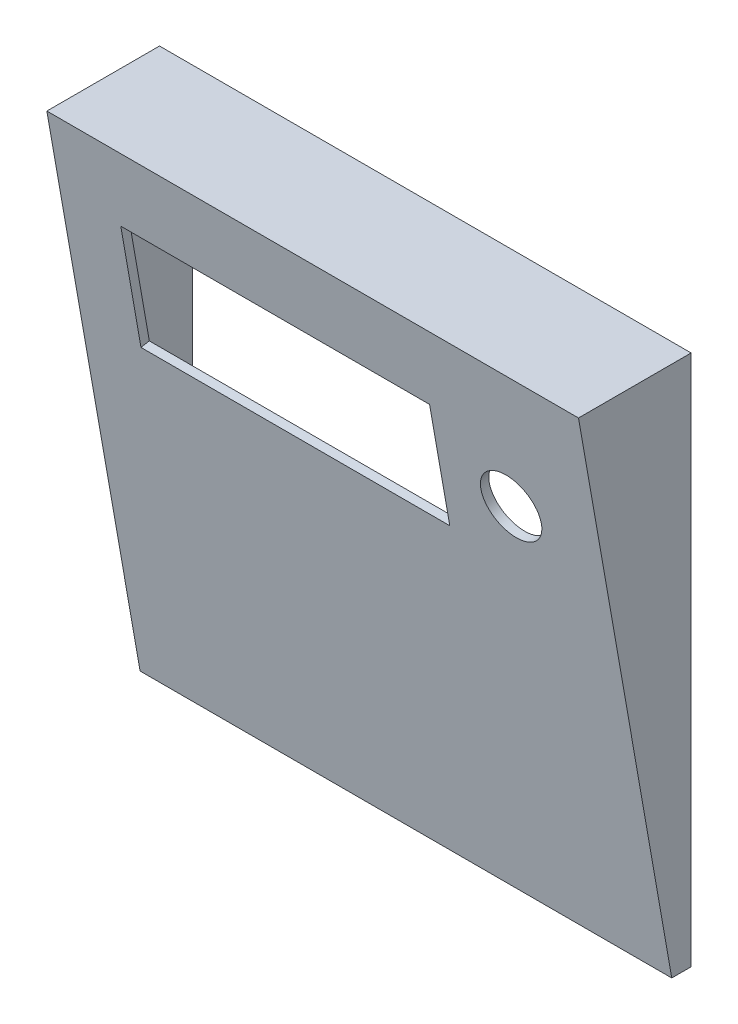
SolidWorks part; units mm, degrees
ref_plane "Front Plane" through (0, 0, 0) normal (0, 0, 1) x (1, 0, 0)
ref_plane "Top Plane" through (0, 0, 0) normal (0, 1, 0) x (1, 0, 0)
ref_plane "Right Plane" through (0, 0, 0) normal (1, 0, 0) x (0, 0, -1)
sketch "Sketch1" plane through (0, 0, 0) normal (0, 0, 1) x (1, 0, 0)
  line L1 (0, 0) -> (87.8, 0)
  line L2 (0, 0) -> (0, 87.8)
  line L3 (0, 87.8) -> (87.8, 87.8)
  line L4 (87.8, 0) -> (87.8, 87.8)
  dimension "D1" = 87.8
extrude "Boss-Extrude1" add sketch "Sketch1" along normal blind 20
sketch "Sketch2" plane through (0, 0, 0) normal (0, 0, -1) x (-1, 0, 0)
  line L0 (0, 0) -> (-87.8, 0) construction
  line L1 (-86.15, 86.15) -> (-1.65, 86.15)
  line L2 (-86.15, 86.15) -> (-86.15, 1.65)
  line L3 (-86.15, 1.65) -> (-1.65, 1.65)
  line L4 (-1.65, 86.15) -> (-1.65, 1.65)
  line L5 (0, 87.8) -> (0, 0) construction
  line L7 (-87.8, 87.8) -> (0, 87.8)
  line L8 (-87.8, 87.8) -> (-87.8, 0)
  line L9 (-87.8, 0) -> (0, 0)
  line L10 (0, 87.8) -> (0, 0)
  point P4 (-43.9, 1.65)
  point P7 (-43.9, 0)
  point P8 (-1.65, 43.9)
  point P11 (0, 43.9)
  dimension "D1" = 84.5
extrude "Cut-Extrude1" cut sketch "Sketch2" against normal blind 1.4
sketch "Sketch3" plane through (87.8, 0, 0) normal (1, 0, 0) x (0, 0, -1)
  line L0 (-20, 87.8) -> (-4.6, 0)
  line L1 (-20, 0) -> (-1.4, 0) construction
  line L2 (-4.6, 0) -> (-20, 0)
  line L3 (-20, 0) -> (-20, 87.8)
  dimension "D1" = 3.2
extrude "Cut-Extrude2" cut sketch "Sketch3" against normal through all
sketch "Sketch4" plane through (0, 0, 0) normal (0, 0, -1) x (-1, 0, 0)
  line L0 (-83.75, 83.75) -> (-83.75, 4.05)
  line L1 (-86.15, 86.15) -> (-1.65, 86.15) construction
  line L2 (-86.15, 86.15) -> (-86.15, 1.65) construction
  line L3 (-86.15, 1.65) -> (-1.65, 1.65) construction
  line L4 (-1.65, 86.15) -> (-1.65, 1.65) construction
  line L5 (-83.75, 4.05) -> (-4.05, 4.05)
  line L6 (-4.05, 83.75) -> (-4.05, 4.05)
  line L7 (-83.75, 83.75) -> (-4.05, 83.75)
  dimension "D1" = 2.4
extrude "Cut-Extrude3" cut sketch "Sketch4" against normal offset from surface (17.8683 mm away) 1.4
sketch "Sketch5" plane through (0, -0.7828, 4.4627) normal (0, -0.1728, 0.985) x (1, 0, 0)
  line L0 (0, 0.7947) -> (0, 89.935) construction
  line L1 (10, 77.1769) -> (61, 77.1769)
  line L2 (10, 77.1769) -> (10, 57.8729)
  line L3 (10, 57.8729) -> (61, 57.8729)
  line L4 (61, 77.1769) -> (61, 57.8729)
  line L5 (87.8, 0.7947) -> (87.8, 89.935) construction
  circle A0 centre (72.8, 67.5249) radius 5
  point P6 (61, 67.5249)
  point P7 (75.4552, 67.5249)
  dimension "D4" = 10
  dimension "D6" = 10
  dimension "D1" = 19.304
  dimension "D2" = 51
  dimension "D3" = 11.8
  dimension "D5" = 10
extrude "Cut-Extrude4" cut sketch "Sketch5" against normal through all
